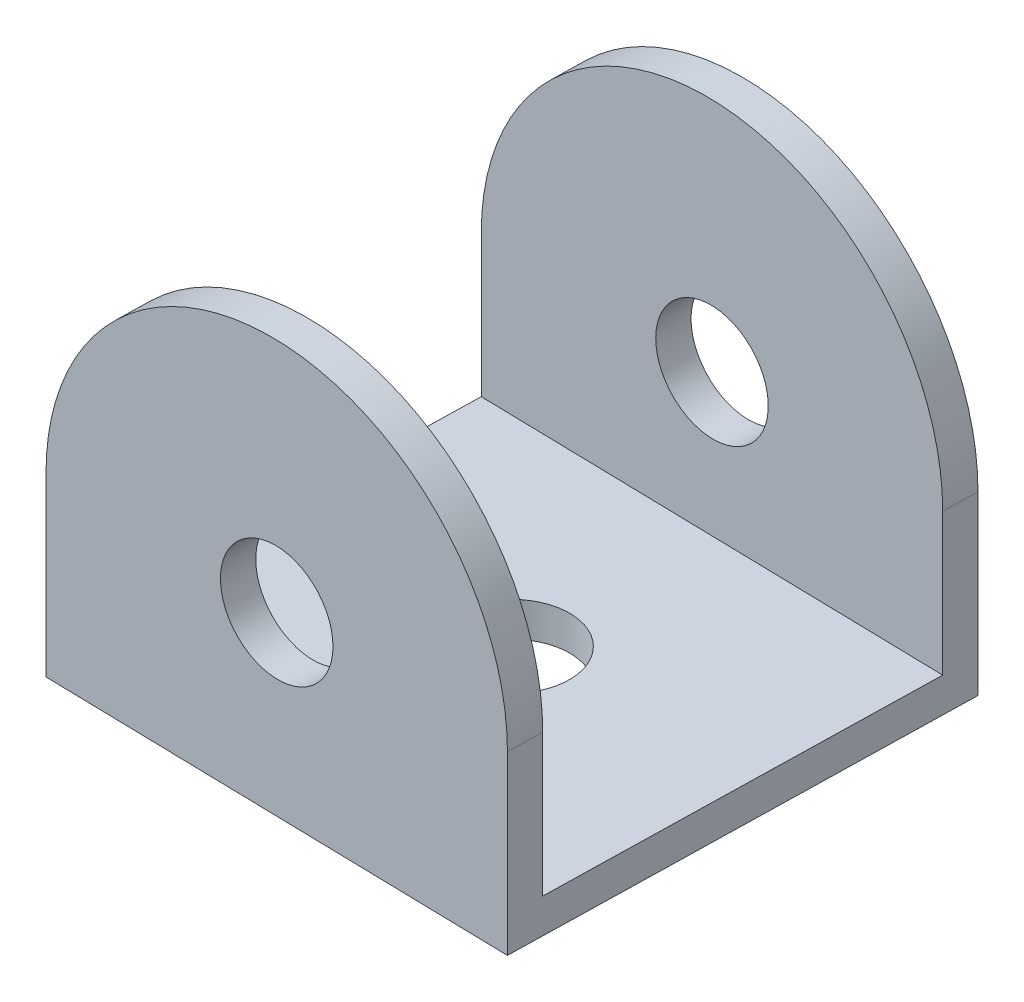
SolidWorks part; units mm, degrees
ref_plane "Front Plane" through (0, 0, 0) normal (0, 0, 1) x (1, 0, 0)
ref_plane "Top Plane" through (0, 0, 0) normal (0, 1, 0) x (1, 0, 0)
ref_plane "Right Plane" through (0, 0, 0) normal (1, 0, 0) x (0, 0, -1)
sketch "Sketch1" plane through (0, 0, 0) normal (0, 1, 0) x (1, 0, 0)
  line L0 (0, 0) -> (40.9899, -0.9081)
  line L1 (40.9899, -0.9081) -> (41.8759, 39.0821)
  line L2 (41.8759, 39.0821) -> (0.8859, 39.9902)
  line L3 (0, 0) -> (0.8859, 39.9902)
extrude "Boss-Extrude1" add sketch "Sketch1" along normal blind 3
sketch "Sketch2" plane through (0, 3, 0) normal (0, 1, 0) x (1, 0, 0)
  line L0 (21.3809, 39.5362) -> (20.9379, 19.5411) construction
  line L1 (41.8759, 39.0821) -> (0.8859, 39.9902) construction
  circle A0 centre (20.9379, 19.5411) radius 5
extrude "Cut-Extrude1" cut sketch "Sketch2" against normal blind 3
sketch "Sketch4" plane through (0, 0, 0) normal (-0.0221, 0, 0.9998) x (0.9998, 0, 0.0221)
  line L0 (0, 3) -> (0, 15.3241)
  line L2 (41, 15.3241) -> (41, 3)
  arc A0 (41, 15.3241) -> (0, 15.3241) centre (20.5, 15.3241) ccw
  circle A1 centre (20.5, 15.3241) radius 5
  line M3 (41, 3) -> (0, 3)
extrude "Boss-Extrude2" add sketch "Sketch4" against normal blind 3 contours L2 A0 L0 A1 M3
sketch "Sketch5" plane through (0.8859, 0, -39.9902) normal (0.0221, 0, -0.9998) x (-0.9998, 0, -0.0221)
  line L0 (-41, 3) -> (-41, 15.3241)
  line L2 (0, 15.3241) -> (0, 3)
  line L3 (0, 3) -> (-41, 3)
  circle A0 centre (-20.5, 15.3241) radius 5
  arc A1 (0, 15.3241) -> (-41, 15.3241) centre (-20.5, 15.3241) ccw
extrude "Boss-Extrude3" add sketch "Sketch5" against normal blind 3
